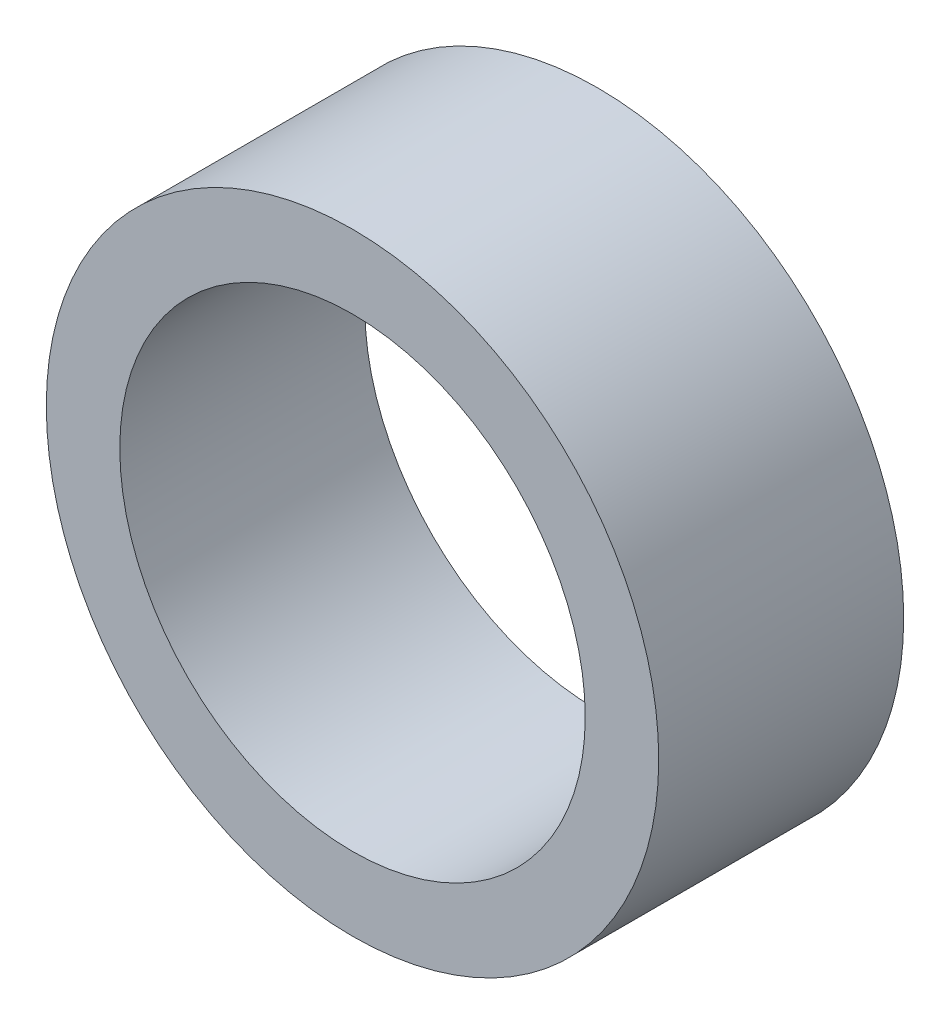
SolidWorks part; units mm, degrees
ref_plane "Front Plane" through (0, 0, 0) normal (0, 0, 1) x (1, 0, 0)
ref_plane "Top Plane" through (0, 0, 0) normal (0, 1, 0) x (1, 0, 0)
ref_plane "Right Plane" through (0, 0, 0) normal (1, 0, 0) x (0, 0, -1)
sketch "Sketch1" plane through (0, 0, 0) normal (0, 0, 1) x (1, 0, 0)
  circle A0 centre (0, 0) radius 12.5
  circle A1 centre (0, 0) radius 9.5
  dimension "D1" = 19
  dimension "D2" = 25
extrude "Boss-Extrude1" add sketch "Sketch1" along normal blind 10
